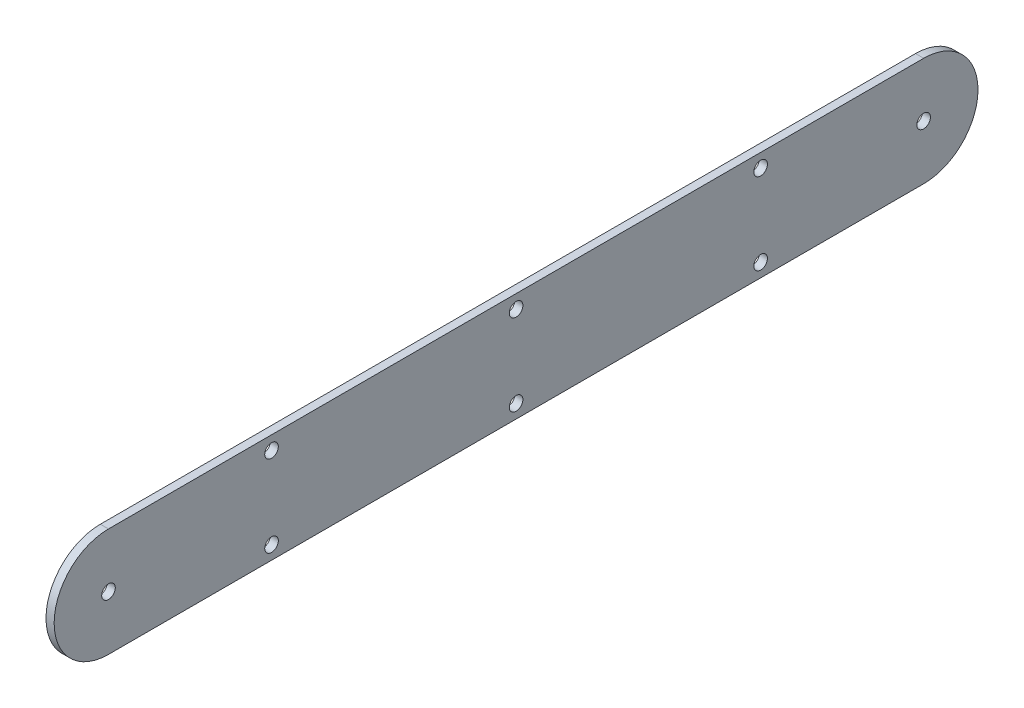
SolidWorks part; units mm, degrees
ref_plane "Front Plane" through (0, 0, 0) normal (0, 0, 1) x (1, 0, 0)
ref_plane "Top Plane" through (0, 0, 0) normal (0, 1, 0) x (1, 0, 0)
ref_plane "Right Plane" through (0, 0, 0) normal (1, 0, 0) x (0, 0, -1)
sketch "Sketch1" plane through (0, 0, 0) normal (1, 0, 0) x (0, 0, -1)
  line L0 (150, 0) -> (-150, 0) construction
  line L1 (-150, -20) -> (150, -20)
  line L2 (-90, 15) -> (223.3324, 15) construction
  line L3 (-150, 20) -> (150, 20)
  line L4 (-90, -15) -> (210.8275, -15) construction
  line L5 (-150, -20) -> (150, 20) construction
  line L6 (-150, 20) -> (150, -20) construction
  arc A0 (150, 20) -> (150, -20) centre (150, 0) cw
  arc A1 (-150, 20) -> (-150, -20) centre (-150, 0) ccw
  circle A2 centre (150, 0) radius 2.5
  circle A3 centre (-150, 0) radius 2.5
  circle A4 centre (90, 15) radius 2.5
  circle A5 centre (90, -15) radius 2.5
  circle A6 centre (-90, 15) radius 2.5
  circle A7 centre (-90, -15) radius 2.5
  circle A8 centre (0, 15) radius 2.5
  circle A9 centre (0, -15) radius 2.5
  point P0 (0, 0)
  dimension "D3" = 5
  dimension "D4" = 5
  dimension "D7" = 5
  dimension "D8" = 5
  dimension "D15" = 5
  dimension "D16" = 5
  dimension "D17" = 5
  dimension "D18" = 5
  dimension "D1" = 300
  dimension "D2" = 40
  dimension "D5" = 60
  dimension "D6" = 0
  dimension "D11" = 60
  dimension "D12" = 0
  dimension "D13" = 30
  dimension "D14" = 15
extrude "Boss-Extrude1" add sketch "Sketch1" along normal blind 3
sketch "Sketch2" plane through (3, 0, 0) normal (1, 0, 0) x (0, 0, -1)
